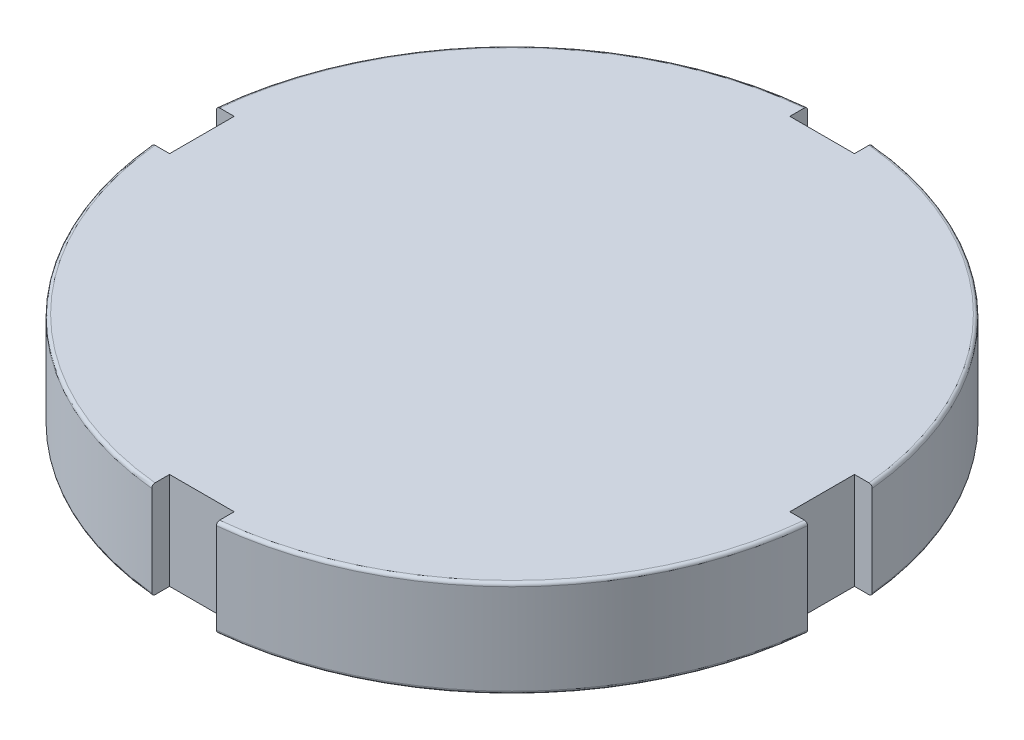
SolidWorks part; units mm, degrees
ref_plane "Front" through (0, 0, 0) normal (0, 0, 1) x (1, 0, 0)
ref_plane "Top" through (0, 0, 0) normal (0, 1, 0) x (1, 0, 0)
ref_plane "Right" through (0, 0, 0) normal (1, 0, 0) x (0, 0, -1)
sketch "Sketch2" plane through (0, 0, 0) normal (0, 1, 0) x (1, 0, 0)
  circle A0 centre (0, 0) radius 64.77
  dimension "D1" = 129.54
extrude "Boss-Extrude1" add sketch "Sketch2" along normal blind 19.05
fillet "Fillet1" radius 0.635 2 edges at (0, 0, 64.77) (0, 19.05, 64.77)
sketch "Sketch3" plane through (0, 19.05, 0) normal (0, 1, 0) x (1, 0, 0)
  circle A0 centre (0, 0) radius 7.62
  dimension "D1" = 15.24
sketch "Sketch4" plane through (0, 0, 0) normal (0, -1, 0) x (1, 0, 0)
  line L0 (-73.4673, 0) -> (74.0346, 0) construction
  line L1 (0, 71.1035) -> (0, -72.2381) construction
  line L2 (-12.7646, 0) -> (-12.7646, -60.96) construction
  line L3 (6.35, -70.0594) -> (-6.35, -70.0594)
  line L4 (-6.35, -70.0594) -> (-6.35, -60.96)
  line L5 (-6.35, -60.96) -> (6.35, -60.96)
  line L6 (6.35, -60.96) -> (6.35, -70.0594)
  line L7 (-60.96, -6.35) -> (-70.0594, -6.35)
  line L8 (-70.0594, -6.35) -> (-70.0594, 6.35)
  line L9 (-70.0594, 6.35) -> (-60.96, 6.35)
  line L10 (-60.96, 6.35) -> (-60.96, -6.35)
  line L11 (-6.35, 60.96) -> (-6.35, 70.0594)
  line L12 (-6.35, 70.0594) -> (6.35, 70.0594)
  line L13 (6.35, 70.0594) -> (6.35, 60.96)
  line L14 (6.35, 60.96) -> (-6.35, 60.96)
  line L15 (60.96, 6.35) -> (70.0594, 6.35)
  line L16 (70.0594, 6.35) -> (70.0594, -6.35)
  line L17 (70.0594, -6.35) -> (60.96, -6.35)
  line L18 (60.96, -6.35) -> (60.96, 6.35)
  point P10 (0, -70.0594)
  point P27 (0, 0)
  dimension "D1" = 60.96
  dimension "D2" = 6.35
  dimension "D3" = 4
extrude "Cut-Extrude2" cut sketch "Sketch4" against normal through all
